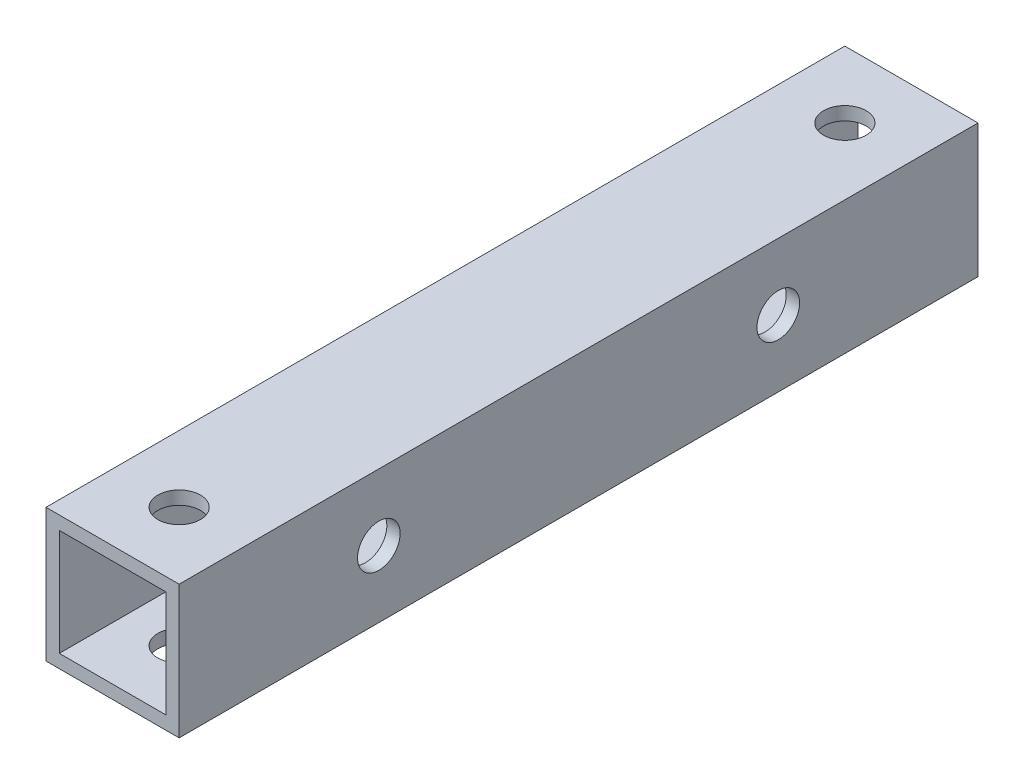
SolidWorks part; units mm, degrees
ref_plane "正面" through (0, 0, 0) normal (0, 0, 1) x (1, 0, 0)
ref_plane "平面" through (0, 0, 0) normal (0, 1, 0) x (1, 0, 0)
ref_plane "右側面" through (0, 0, 0) normal (1, 0, 0) x (0, 0, -1)
sketch "ｽｹｯﾁ1" plane through (0, 0, 0) normal (0, 0, 1) x (1, 0, 0)
  line L1 (-5, 5) -> (5, 5)
  line L2 (-5, 5) -> (-5, -5)
  line L3 (-5, -5) -> (5, -5)
  line L4 (5, 5) -> (5, -5)
  line L5 (-5, 5) -> (5, -5) construction
  line L6 (-5, -5) -> (5, 5) construction
  point P0 (0, 0)
  dimension "D1" = 10
  dimension "D2" = 10
extrude "押し出し-薄板1" add sketch "ｽｹｯﾁ1" along normal mid plane 60 thin
sketch "ｽｹｯﾁ2" plane through (0, 5, 0) normal (0, 1, 0) x (1, 0, 0)
  line L0 (5, -30) -> (5, 30) construction
  line L1 (5, 30) -> (-5, 30) construction
  circle A0 centre (0, 25) radius 1.6
  dimension "D3" = 3.2
  dimension "D1" = 5
  dimension "D2" = 5
extrude "ｶｯﾄ - 押し出し1" cut sketch "ｽｹｯﾁ2" against normal through all both and the other way through all
sketch "ｽｹｯﾁ3" plane through (-5, 0, 0) normal (-1, 0, 0) x (0, 0, 1)
  line L0 (-30, 5) -> (-30, -5) construction
  line L1 (30, 5) -> (-30, 5) construction
  circle A0 centre (-15, 0) radius 1.6
  dimension "D1" = 15
  dimension "D2" = 5
  dimension "D3" = 3.2
extrude "ｶｯﾄ - 押し出し2" cut sketch "ｽｹｯﾁ3" against normal through all both
mirror "ﾐﾗｰ1" about plane through (0, 0, 0) normal (0, 0, 1) of "ｶｯﾄ - 押し出し2", "ｶｯﾄ - 押し出し1"
